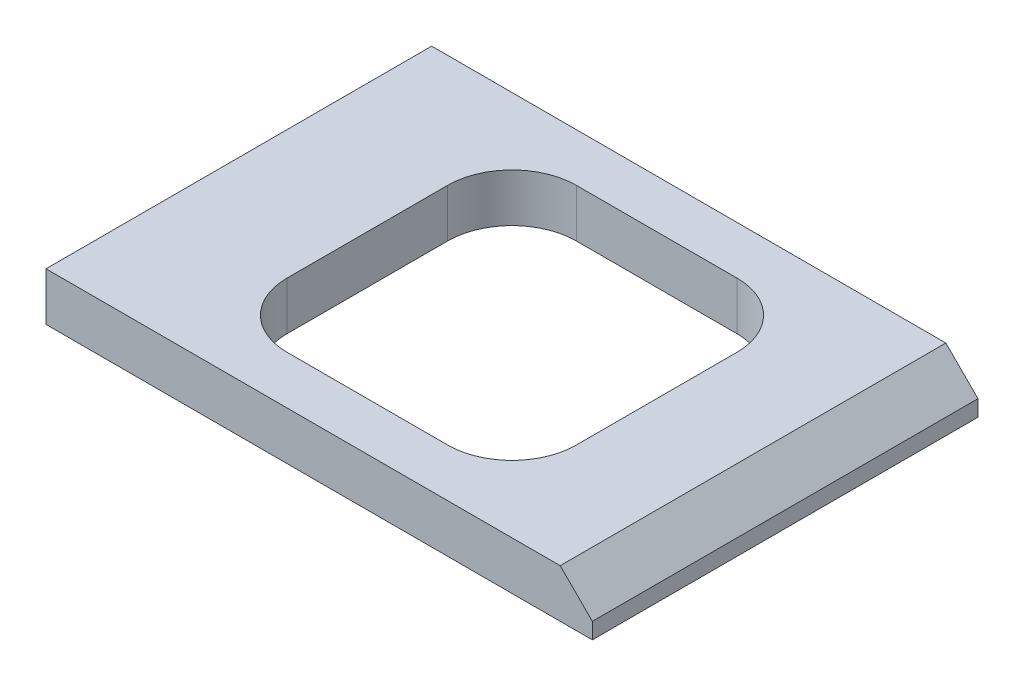
SolidWorks part; units mm, degrees
material "6061 Alloy"
ref_plane "Front Plane" through (0, 0, 0) normal (0, 0, 1) x (1, 0, 0)
ref_plane "Top Plane" through (0, 0, 0) normal (0, 1, 0) x (1, 0, 0)
ref_plane "Right Plane" through (0, 0, 0) normal (1, 0, 0) x (0, 0, -1)
sketch "Sketch1" plane through (0, 0, 0) normal (0, 1, 0) x (1, 0, 0)
  line L1 (26.9875, -19.05) -> (-26.9875, -19.05)
  line L2 (26.9875, -19.05) -> (26.9875, 19.05)
  line L3 (26.9875, 19.05) -> (-26.9875, 19.05)
  line L4 (-26.9875, -19.05) -> (-26.9875, 19.05)
  line L5 (26.9875, -19.05) -> (-26.9875, 19.05) construction
  line L6 (26.9875, 19.05) -> (-26.9875, -19.05) construction
  point P0 (0, 0)
  dimension "D1" = 38.1
  dimension "D2" = 53.975
extrude "Boss-Extrude1" add sketch "Sketch1" along normal mid plane 4.7625
hole_wizard "1 (1) Diameter Hole2" positions "Sketch2" profile "Sketch3" hole size "1" standard "ANSI Inch"
sketch "Sketch2" plane through (0, 2.3813, 0) normal (0, 1, 0) x (1, 0, 0)
  line L0 (-26.9875, 19.05) -> (-26.9875, -19.05) construction
  point P0 (0, 0)
  dimension "D1" = 26.9875
sketch "Sketch3" plane through (0, 2.3813, 0) normal (1, 0, 0) x (0, 0, 1)
  line L0 (0, 0) -> (0, 4.7625)
  line L1 (0, 4.7625) -> (12.7, 4.7625)
  line L2 (12.7, 4.7625) -> (12.7, 0)
  line L5 (12.7, 0) -> (0, 0)
  line L11 (0, -6.35) -> (0, 107.95) construction
  dimension "Thru Hole Dia." = 25.4
  dimension "Thru Hole Depth" = 4.7625
chamfer "Chamfer1" distance 3.175 angle 45 1 edges at (26.9875, 2.3813, 0)
sketch "Sketch4" plane through (0, 2.3813, 0) normal (0, 1, 0) x (1, 0, 0)
  line L1 (14.2875, 14.2875) -> (-14.2875, 14.2875)
  line L2 (14.2875, 14.2875) -> (14.2875, -14.2875)
  line L3 (14.2875, -14.2875) -> (-14.2875, -14.2875)
  line L4 (-14.2875, 14.2875) -> (-14.2875, -14.2875)
  line L5 (14.2875, 14.2875) -> (-14.2875, -14.2875) construction
  line L6 (14.2875, -14.2875) -> (-14.2875, 14.2875) construction
  point P0 (0, 0)
  dimension "D1" = 28.575
  dimension "D2" = 28.575
extrude "Cut-Extrude1" cut sketch "Sketch4" against normal through all both and the other way through all
fillet "Fillet1" radius 6.35 4 edges at (14.2875, 0, -14.2875) (14.2875, 0, 14.2875) (-14.2875, 0, -14.2875) (-14.2875, 0, 14.2875)
